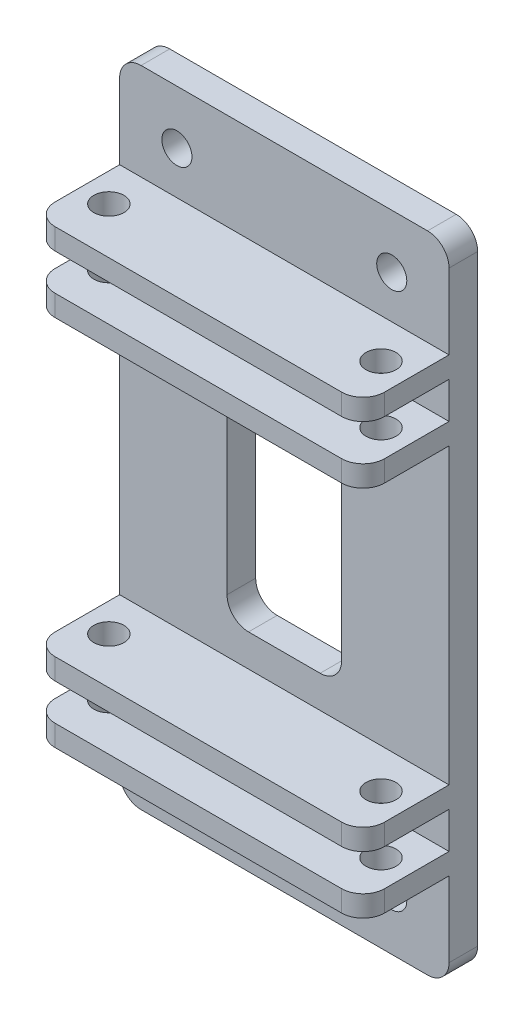
SolidWorks part; units mm, degrees
material "7075-T6，板材(SS)"
ref_plane "前视基准面" through (0, 0, 0) normal (0, 0, 1) x (1, 0, 0)
ref_plane "上视基准面" through (0, 0, 0) normal (0, 1, 0) x (1, 0, 0)
ref_plane "右视基准面" through (0, 0, 0) normal (1, 0, 0) x (0, 0, -1)
sketch "草图1" plane through (0, 0, 0) normal (0, 0, 1) x (1, 0, 0)
  line L1 (-20, -45) -> (20, -45)
  line L2 (-23, -42) -> (-23, 42)
  line L3 (-20, 45) -> (20, 45)
  line L4 (23, -42) -> (23, 42)
  line L5 (-23, -45) -> (23, 45) construction
  line L6 (-23, 45) -> (23, -45) construction
  arc A0 (20, -45) -> (23, -42) centre (20, -42) ccw
  arc A1 (-23, 42) -> (-20, 45) centre (-20, 42) cw
  arc A2 (-20, -45) -> (-23, -42) centre (-20, -42) cw
  arc A3 (20, 45) -> (23, 42) centre (20, 42) cw
  point P0 (0, 0)
  dimension "D3" = 3
  dimension "D1" = 46
  dimension "D2" = 90
extrude "凸台-拉伸1" add sketch "草图1" along normal blind 4
sketch "草图2" plane through (0, 0, 4) normal (0, 0, 1) x (1, 0, 0)
  line L1 (-15, -37.5) -> (15, -37.5) construction
  line L2 (-15, -37.5) -> (-15, 37.5) construction
  line L3 (-15, 37.5) -> (15, 37.5) construction
  line L4 (15, -37.5) -> (15, 37.5) construction
  line L5 (-15, -37.5) -> (15, 37.5) construction
  line L6 (-15, 37.5) -> (15, -37.5) construction
  circle A0 centre (15, -37.5) radius 2.1
  circle A1 centre (-15, -37.5) radius 2.1
  circle A2 centre (-15, 37.5) radius 2.1
  circle A3 centre (15, 37.5) radius 2.1
  point P0 (0, 0)
  dimension "D3" = 4.2
  dimension "D1" = 75
  dimension "D2" = 30
extrude "切除-拉伸1" cut sketch "草图2" against normal blind 4
sketch "草图3" plane through (0, 0, 4) normal (0, 0, 1) x (1, 0, 0)
  line L0 (23, -42) -> (23, 42) construction
  line L1 (-23, 20.5) -> (23, 20.5)
  line L2 (-23, 20.5) -> (-23, 31.5)
  line L3 (-23, 31.5) -> (23, 31.5)
  line L4 (23, 20.5) -> (23, 31.5)
  line L5 (-23, 20.5) -> (23, 31.5) construction
  line L6 (-23, 31.5) -> (23, 20.5) construction
  line L7 (20, 45) -> (-20, 45) construction
  line L9 (-23, 23.45) -> (23, 23.45)
  line L10 (-23, 23.45) -> (-23, 28.55)
  line L11 (-23, 28.55) -> (23, 28.55)
  line L12 (23, 23.45) -> (23, 28.55)
  line L13 (-23, 23.45) -> (23, 28.55) construction
  line L14 (-23, 28.55) -> (23, 23.45) construction
  point P0 (0, 26)
  point P11 (0, 26)
  line M9 (23, -42) -> (23, 42)
  line M13 (-23, 42) -> (-23, -42)
  dimension "D1" = 19
  dimension "D2" = 11
  dimension "D3" = 5.1
extrude "凸台-拉伸2" add sketch "草图3" along normal blind 12 contours L11 L3 M13 M9 | L9 L2 L1 M9
mirror "镜向1" about plane through (0, 0, 0) normal (0, 1, 0) of "凸台-拉伸2"
fillet "圆角1" radius 3 8 edges at (-23, 30.025, 16) (23, 30.025, 16) (-23, 21.975, 16) (23, 21.975, 16) (23, -21.975, 16) (-23, -21.975, 16) (-23, -30.025, 16) (23, -30.025, 16)
sketch "草图4" plane through (0, -31.5, 0) normal (0, -1, 0) x (1, 0, 0)
  line L0 (-19, 9.5) -> (19, 9.5) construction
  line L1 (-23, 4) -> (23, 4) construction
  circle A0 centre (19, 9.5) radius 2.1
  circle A1 centre (-19, 9.5) radius 2.1
  point P3 (0, 9.5)
  dimension "D3" = 4.2
  dimension "D1" = 5.5
  dimension "D2" = 38
extrude "切除-拉伸2" cut sketch "草图4" against normal through all
sketch "草图5" plane through (0, 0, 0) normal (0, 0, -1) x (-1, 0, 0)
  line L1 (-5, -16) -> (5, -16)
  line L2 (-8, -13) -> (-8, 13)
  line L3 (-5, 16) -> (5, 16)
  line L4 (8, -13) -> (8, 13)
  line L5 (-8, -16) -> (8, 16) construction
  line L6 (-8, 16) -> (8, -16) construction
  arc A0 (5, -16) -> (8, -13) centre (5, -13) ccw
  arc A1 (-8, 13) -> (-5, 16) centre (-5, 13) cw
  arc A2 (-5, -16) -> (-8, -13) centre (-5, -13) cw
  arc A3 (5, 16) -> (8, 13) centre (5, 13) cw
  point P0 (0, 0)
  dimension "D3" = 3
  dimension "D1" = 16
  dimension "D2" = 32
extrude "切除-拉伸3" cut sketch "草图5" against normal blind 10
